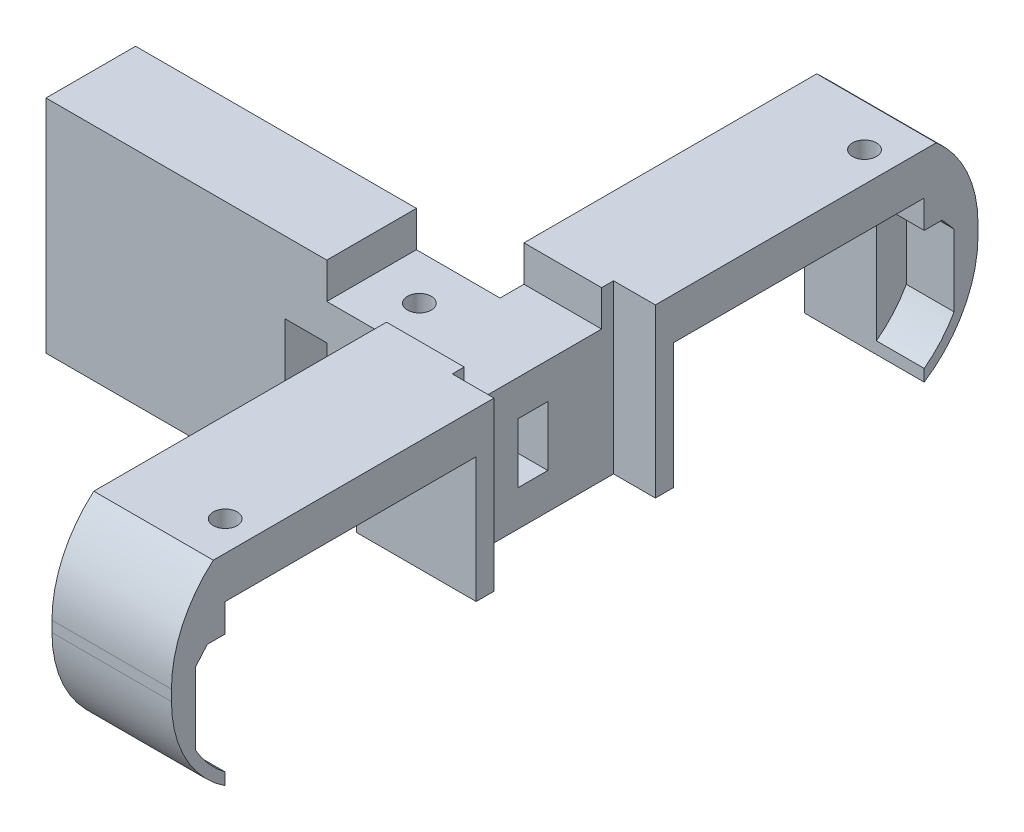
SolidWorks part; units mm, degrees
material "ABS"
ref_plane "Front Plane" through (0, 0, 0) normal (0, 0, 1) x (1, 0, 0)
ref_plane "Top Plane" through (0, 0, 0) normal (0, 1, 0) x (1, 0, 0)
ref_plane "Right Plane" through (0, 0, 0) normal (1, 0, 0) x (0, 0, -1)
sketch "Sketch1" plane through (0, 0, 0) normal (0, 1, 0) x (1, 0, 0)
  line L1 (-15.3176, 43.2333) -> (45.6824, 43.2333)
  line L2 (45.6824, 43.2333) -> (45.6824, -16.7667)
  line L3 (45.6824, -16.7667) -> (65.6824, -16.7667)
  line L4 (65.6824, -16.7667) -> (65.6824, 118.2333)
  line L7 (-15.3176, 43.2333) -> (-15.3176, 58.2333)
  line L8 (-15.3176, 58.2333) -> (45.6824, 58.2333)
  line L9 (45.6824, 58.2333) -> (45.6824, 118.2333)
  line L10 (45.6824, 118.2333) -> (65.6824, 118.2333)
  dimension "D1" = 20
  dimension "D2" = 60
  dimension "D3" = 61
  dimension "D4" = 15
  dimension "D5" = 60
  dimension "D6" = 20
extrude "Boss-Extrude1" add sketch "Sketch1" along normal blind 37
sketch "Sketch2" plane through (65.6824, 0, 0) normal (1, 0, 0) x (0, 0, -1)
  line L1 (-7.7667, 30) -> (34.2333, 30)
  line L2 (-7.7667, 30) -> (-7.7667, 9)
  line L3 (-7.7667, 9) -> (34.2333, 9)
  line L4 (34.2333, 30) -> (34.2333, 9)
  line L5 (-16.7667, 37) -> (-16.7667, 0) construction
  line L6 (50.7333, 26.6294) -> (50.7333, 61.3446) construction
  line L7 (-16.7667, 0) -> (118.2333, 0) construction
  line L9 (109.2333, 9) -> (67.2333, 9)
  line L10 (109.2333, 30) -> (109.2333, 9)
  line L11 (109.2333, 30) -> (67.2333, 30)
  line L12 (67.2333, 30) -> (67.2333, 9)
  dimension "D1" = 21
  dimension "D2" = 42
  dimension "D3" = 9
  dimension "D4" = 9
  dimension "D5" = 7.5
extrude "Cut-Extrude1" cut sketch "Sketch2" against normal up to next
sketch "Sketch3" plane through (45.6824, 0, 0) normal (-1, 0, 0) x (0, 0, 1)
  line L0 (7.7667, 9) -> (7.7667, 30) construction
  line L1 (-34.2333, 9) -> (7.7667, 9) construction
  line L2 (-50.7333, 34.1987) -> (-50.7333, 62.1119) construction
  line L3 (-43.2333, 37) -> (-43.2333, 0) construction
  circle A0 centre (11.2667, 24.75) radius 2
  circle A1 centre (11.2667, 15.25) radius 2
  circle A2 centre (-37.7333, 24.75) radius 2
  circle A3 centre (-37.7333, 15.25) radius 2
  circle A4 centre (-112.7333, 24.75) radius 2
  circle A5 centre (-112.7333, 15.25) radius 2
  circle A6 centre (-63.7333, 15.25) radius 2
  circle A7 centre (-63.7333, 24.75) radius 2
  dimension "D1" = 4
  dimension "D2" = 49
  dimension "D3" = 9.5
  dimension "D4" = 3.5
  dimension "D5" = 6.25
  dimension "D6" = 7.5
extrude "Cut-Extrude2" cut sketch "Sketch3" against normal blind 10
fillet "Fillet1" radius 20 2 edges at (55.6824, 0, 16.7667) (55.6824, 0, -118.2333)
sketch "Sketch6" plane through (65.6824, 0, 0) normal (1, 0, 0) x (0, 0, -1)
  line L0 (34.2333, 9) -> (34.2333, 30) construction
  line L1 (-7.7667, 9) -> (34.2333, 9)
  line L2 (-7.7667, 9) -> (-7.7667, 0)
  line L3 (-7.7667, 0) -> (34.2333, 0)
  line L4 (34.2333, 9) -> (34.2333, 0)
  line L5 (3.2333, 0) -> (98.2333, 0) construction
  line L6 (50.7333, 26.0053) -> (50.7333, 53.0852) construction
  line L7 (67.2333, 9) -> (67.2333, 0)
  line L8 (109.2333, 9) -> (67.2333, 9)
  line L9 (109.2333, 0) -> (67.2333, 0)
  line L10 (109.2333, 9) -> (109.2333, 0)
  dimension "D1" = 7.5
extrude "Cut-Extrude5" cut sketch "Sketch6" against normal up to next
sketch "Sketch7" plane through (-15.3176, 0, 0) normal (-1, 0, 0) x (0, 0, 1)
  line L2 (-58.2333, 37) -> (-43.2333, 37) construction
  line L3 (-43.2333, 37) -> (-43.2333, 0) construction
  circle A0 centre (-50.7333, 27) radius 2
  circle A1 centre (-50.7333, 12) radius 2
  dimension "D1" = 4
  dimension "D3" = 15
  dimension "D4" = 10
  dimension "D5" = 7.5
extrude "Cut-Extrude6" cut sketch "Sketch7" against normal blind 10
sketch "Sketch8" plane through (0, 0, 0) normal (0, -1, 0) x (1, 0, 0)
  line L1 (45.6824, -67.2333) -> (45.6824, -58.2333) construction
  line L2 (45.6824, -67.2333) -> (65.6824, -67.2333) construction
  line L3 (65.6824, -34.2333) -> (65.6824, -67.2333) construction
  line L4 (45.6824, -34.2333) -> (65.6824, -34.2333) construction
  line L5 (45.6824, -43.2333) -> (45.6824, -34.2333) construction
  line L9 (45.6824, -67.2333) -> (45.6824, -58.2333)
  line L10 (45.6824, -67.2333) -> (65.6824, -67.2333)
  line L11 (65.6824, -34.2333) -> (65.6824, -67.2333)
  line L12 (45.6824, -34.2333) -> (65.6824, -34.2333)
  line L13 (45.6824, -43.2333) -> (45.6824, -34.2333)
  line L16 (45.6824, -43.2333) -> (25.6824, -43.2333)
  line L17 (-15.3176, -43.2333) -> (45.6824, -43.2333) construction
  line L18 (25.6824, -43.2333) -> (25.6824, -58.2333)
  line L19 (45.6824, -58.2333) -> (-15.3176, -58.2333) construction
  line L20 (25.6824, -58.2333) -> (45.6824, -58.2333)
  dimension "D1" = 20
extrude "Cut-Extrude7" cut sketch "Sketch8" against normal blind 9
sketch "Sketch9" plane through (0, 9, 0) normal (0, -1, 0) x (1, 0, 0)
  line L0 (25.6824, -58.2333) -> (45.6824, -58.2333) construction
  line L1 (65.6824, -34.2333) -> (45.6824, -34.2333) construction
  line L2 (65.6824, -67.2333) -> (65.6824, -34.2333) construction
  line L3 (45.6824, -67.2333) -> (65.6824, -67.2333) construction
  circle A0 centre (55.6824, -42.2333) radius 2
  circle A1 centre (55.6824, -59.2333) radius 2
  circle A2 centre (35.6824, -50.7333) radius 2
  dimension "D1" = 4
  dimension "D2" = 7.5
  dimension "D3" = 30
  dimension "D4" = 10
  dimension "D5" = 8
  dimension "D6" = 8
extrude "Cut-Extrude8" cut sketch "Sketch9" against normal blind 10
sketch "Sketch10" plane through (0, 37, 0) normal (0, 1, 0) x (1, 0, 0)
  line L0 (45.6824, 62.2333) -> (65.6824, 62.2333)
  line L1 (45.6824, 118.2333) -> (45.6824, 58.2333) construction
  line L2 (65.6824, -16.7667) -> (65.6824, 118.2333) construction
  line L3 (65.6824, 62.2333) -> (65.6824, 39.2333)
  line L4 (65.6824, 39.2333) -> (45.6824, 39.2333)
  line L5 (45.6824, 43.2333) -> (45.6824, -16.7667) construction
  line L7 (45.6824, 39.2333) -> (45.6824, 43.2333)
  line L8 (45.6824, 43.2333) -> (31.6824, 43.2333)
  line L9 (-15.3176, 43.2333) -> (45.6824, 43.2333) construction
  line L10 (31.6824, 43.2333) -> (31.6824, 58.2333)
  line L11 (45.6824, 58.2333) -> (-15.3176, 58.2333) construction
  line L12 (31.6824, 58.2333) -> (45.6824, 58.2333)
  line L13 (45.6824, 58.2333) -> (45.6824, 62.2333)
  dimension "D1" = 5
  dimension "D2" = 5
  dimension "D3" = 14
extrude "Cut-Extrude9" cut sketch "Sketch10" against normal blind 6
sketch "Sketch11" plane through (0, 31, 0) normal (0, 1, 0) x (1, 0, 0)
  line L1 (45.6824, 58.2333) -> (31.6824, 58.2333) construction
  circle A2 centre (39.6824, 50.7333) radius 2
  dimension "D1" = 4
  dimension "D3" = 7.5
  dimension "D4" = 6
extrude "Cut-Extrude10" cut sketch "Sketch11" against normal blind 9
sketch "Sketch12" plane through (0, 37, 0) normal (0, 1, 0) x (1, 0, 0)
  line L0 (65.6824, 118.2333) -> (45.6824, 118.2333) construction
  line L1 (45.6824, -16.7667) -> (65.6824, -16.7667) construction
  line L2 (65.6824, -16.7667) -> (65.6824, 39.2333) construction
  line L3 (65.6824, 62.2333) -> (65.6824, 118.2333) construction
  circle A0 centre (60.6824, -2.7667) radius 2
  circle A1 centre (60.6824, 104.2333) radius 2
  dimension "D2" = 4
  dimension "D1" = 14
  dimension "D3" = 14
  dimension "D4" = 5
  dimension "D5" = 5
extrude "Cut-Extrude11" cut sketch "Sketch12" against normal blind 10
sketch "Sketch13" plane through (45.6824, 0, 0) normal (-1, 0, 0) x (0, 0, 1)
  line L0 (-39.2333, 37) -> (16.7667, 37) construction
  line L1 (16.7667, 37) -> (16.7667, 20) construction
  line L2 (-118.2333, 37) -> (-62.2333, 37) construction
  line L3 (-118.2333, 37) -> (-118.2333, 20) construction
  line L4 (-111.2333, 37) -> (-118.2333, 37)
  line L5 (-118.2333, 37) -> (-118.2333, 21.8013)
  line L6 (9.7667, 37) -> (16.7667, 37)
  line L7 (16.7667, 37) -> (16.7667, 21.8013)
  arc A0 (9.7667, 37) -> (16.7667, 21.8013) centre (-3.2333, 21.8013) cw
  arc A1 (-111.2333, 37) -> (-118.2333, 21.8013) centre (-98.2333, 21.8013) ccw
  dimension "D1" = 20
  dimension "D3" = 7
  dimension "D4" = 20
  dimension "D2" = 7
extrude "Cut-Extrude12" cut sketch "Sketch13" against normal up to next
sketch "Sketch14" plane through (0, 37, 0) normal (0, 1, 0) x (1, 0, 0)
  line L0 (65.6824, 62.2333) -> (65.6824, 111.2333) construction
  line L1 (65.6824, 64.2333) -> (58.6824, 64.2333)
  line L2 (65.6824, 64.2333) -> (65.6824, 37.2333)
  line L3 (65.6824, 37.2333) -> (58.6824, 37.2333)
  line L4 (58.6824, 64.2333) -> (58.6824, 37.2333)
  line L5 (65.6824, 62.2333) -> (45.6824, 62.2333) construction
  dimension "D1" = 27
  dimension "D2" = 2
  dimension "D3" = 7
extrude "Cut-Extrude16" cut sketch "Sketch14" against normal up to next
sketch "Sketch16" plane through (0, 0, -43.2333) normal (0, 0, 1) x (1, 0, 0)
  line L0 (45.6824, 31) -> (45.6824, 9) construction
  line L1 (24.6824, 25) -> (31.6824, 25)
  line L2 (24.6824, 25) -> (24.6824, 15)
  line L3 (24.6824, 15) -> (31.6824, 15)
  line L4 (31.6824, 25) -> (31.6824, 15)
  line L5 (45.6824, 9) -> (25.6824, 9) construction
  point P4 (31.9846, 24.822)
  dimension "D3" = 14
  dimension "D4" = 6
  dimension "D1" = 10
  dimension "D2" = 7
extrude "Cut-Extrude17" cut sketch "Sketch16" against normal up to next
sketch "Sketch15" plane through (58.6824, 0, 0) normal (1, 0, 0) x (0, 0, -1)
  line L1 (53.2333, 15) -> (48.2333, 15)
  line L2 (53.2333, 15) -> (53.2333, 25)
  line L3 (53.2333, 25) -> (48.2333, 25)
  line L4 (48.2333, 15) -> (48.2333, 25)
  line L5 (37.2333, 9) -> (37.2333, 37) construction
  line L7 (64.2333, 9) -> (37.2333, 9) construction
  dimension "D1" = 5
  dimension "D3" = 10
  dimension "D2" = 11
  dimension "D4" = 6
extrude "Cut-Extrude18" cut sketch "Sketch15" against normal up to next
chamfer "Chamfer1" distance 4.5 angle 60 2 edges at (31.6824, 20, -53.2333) (31.6824, 20, -48.2333)
sketch "Sketch18" plane through (65.6824, 0, 0) normal (1, 0, 0) x (0, 0, -1)
  line L0 (109.2333, 25.2967) -> (112.2333, 25.2967)
  line L2 (112.2333, 25.2967) -> (114.2333, 22.9896)
  line L3 (114.2333, 22.9896) -> (114.2333, 10.9896)
  line L4 (109.2333, 25.2967) -> (109.2333, 5.2967)
  line L5 (109.2333, 3.2967) -> (109.2333, 30) construction
  line L6 (50.7348, 38.3) -> (50.7348, 12.0574) construction
  line L8 (-7.7637, 25.2967) -> (-7.7637, 5.2967)
  line L9 (-12.7637, 22.9896) -> (-12.7637, 10.9896)
  line L10 (-10.7637, 25.2967) -> (-12.7637, 22.9896)
  line L11 (-7.7637, 25.2967) -> (-10.7637, 25.2967)
  arc A1 (114.2333, 10.9896) -> (109.2333, 5.2967) centre (98.2333, 20) cw
  arc A2 (109.2333, 3.2967) -> (118.2333, 20) centre (98.2333, 20) ccw construction
  arc A3 (-12.7637, 10.9896) -> (-7.7637, 5.2967) centre (3.2363, 20) ccw
  dimension "D1" = 20
  dimension "D2" = 2
  dimension "D3" = 5
  dimension "D4" = 3
  dimension "D5" = 12
extrude "Cut-Extrude19" cut sketch "Sketch18" against normal blind 8
equation "\"D3@Sketch12\"=\"D1@Sketch12\""
equation "\"D2@Sketch14\"=(\"D1@Sketch14\"-23)/2"
equation "\"D2@Sketch15\"=(27-\"D1@Sketch15\")/2"
equation "\"D4@Sketch15\"=(22-\"D3@Sketch15\")/2"
equation "\"D4@Sketch16\"=(22-\"D1@Sketch16\")/2"
